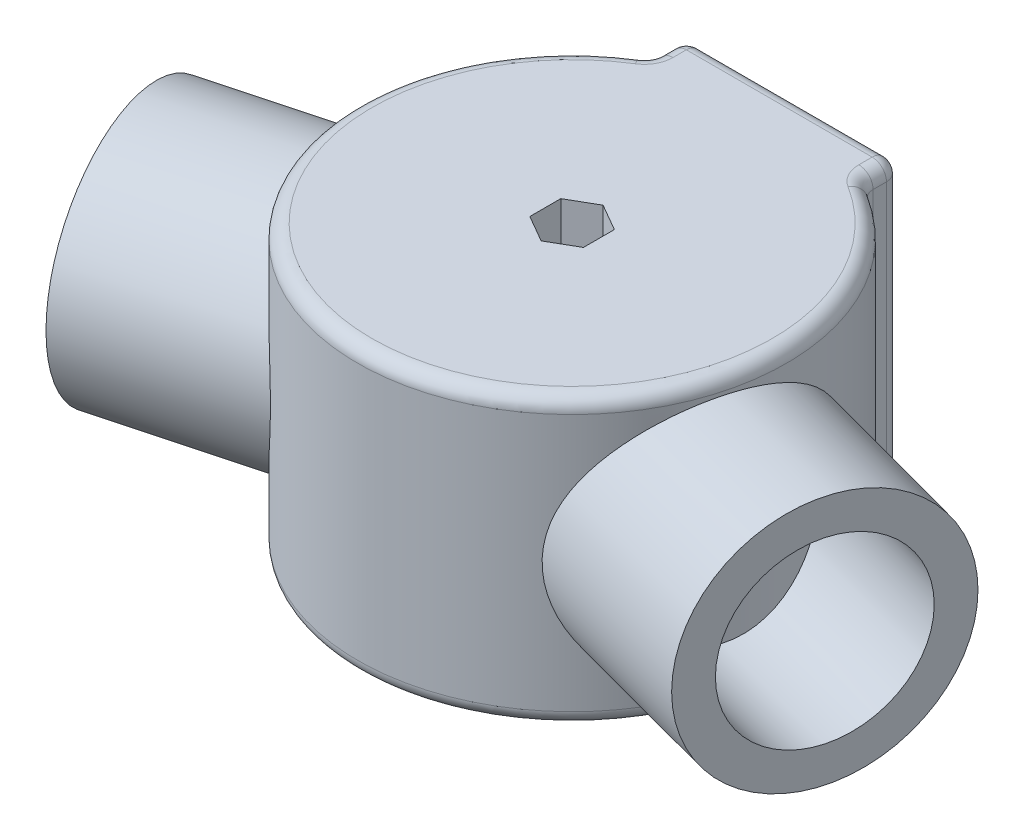
SolidWorks part; units mm, degrees
ref_plane "Front" through (0, 0, 0) normal (0, 0, 1) x (1, 0, 0)
ref_plane "Top" through (0, 0, 0) normal (0, 1, 0) x (1, 0, 0)
ref_plane "Right" through (0, 0, 0) normal (1, 0, 0) x (0, 0, -1)
sketch "Sketch1" plane through (0, 0, 0) normal (0, 1, 0) x (1, 0, 0)
  line L0 (0, 0) -> (0, 39.3456) construction
  line L1 (-19.05, 32.9956) -> (19.05, 32.9956)
  line L2 (-19.05, 32.9956) -> (-19.05, 39.3456)
  line L3 (-19.05, 39.3456) -> (19.05, 39.3456)
  line L4 (19.05, 32.9956) -> (19.05, 39.3456)
  line L6 (0, -5.4993) -> (4.7625, -2.7496)
  line L7 (4.7625, -2.7496) -> (4.7625, 2.7496)
  line L8 (4.7625, 2.7496) -> (0, 5.4993)
  line L9 (0, 5.4993) -> (-4.7625, 2.7496)
  line L10 (-4.7625, 2.7496) -> (-4.7625, -2.7496)
  line L11 (-4.7625, -2.7496) -> (0, -5.4993)
  circle A0 centre (0, 0) radius 38.1
  circle A1 centre (0, 0) radius 4.7625 construction
  dimension "D1" = 76.2
  dimension "D4" = 9.525
  dimension "D2" = 6.35
  dimension "D3" = 38.1
extrude "Boss-Extrude1" add sketch "Sketch1" along normal mid plane 50.8
sketch "Sketch2" plane through (0, 0, 0) normal (0, 1, 0) x (1, 0, 0)
  line L0 (53.9037, -14.4434) -> (0, 0) construction
  line L1 (0, 0) -> (-53.9037, -14.4434) construction
  line L2 (53.9037, -14.4434) -> (-53.9037, -14.4434) construction
  line L6 (-19.05, 39.3456) -> (-19.05, 32.9956)
  line L7 (19.05, 39.3456) -> (-19.05, 39.3456)
  line L8 (19.05, 32.9956) -> (19.05, 39.3456)
  line L9 (-19.05, 39.3456) -> (-19.05, 32.9956)
  line L10 (19.05, 39.3456) -> (-19.05, 39.3456)
  line L11 (19.05, 32.9956) -> (19.05, 39.3456)
  arc A0 (-19.05, 32.9956) -> (19.05, 32.9956) centre (0, 0) ccw construction
  arc A1 (-19.05, 32.9956) -> (19.05, 32.9956) centre (0, 0) ccw
  arc A2 (-19.05, 32.9956) -> (19.05, 32.9956) centre (0, 0) ccw
  point P1 (-36.8018, -9.861)
  point P5 (36.8018, -9.861)
  dimension "D1" = 150
  dimension "D2" = 0
ref_plane "Plane1" through (36.8018, 0, 9.861) normal (-0.9659, 0, -0.2588) x (-0.2588, 0, 0.9659)
sketch "Sketch3" plane through (36.8018, 0, 9.861) normal (-0.9659, 0, -0.2588) x (-0.2588, 0, 0.9659)
  circle A0 centre (0, 0) radius 15.875
  circle A1 centre (0, 0) radius 22.225
  dimension "D1" = 31.75
  dimension "D2" = 6.35
extrude "Boss-Extrude2" add sketch "Sketch3" against normal blind 25.4 and the other way blind 8.255
mirror "Mirror1" about plane through (0, 0, 0) normal (1, 0, 0) of "Boss-Extrude2"
sketch "Sketch5" plane through (0, 0, -39.3456) normal (0, 0, -1) x (-1, 0, 0)
  line L1 (-19.05, 12.7) -> (19.05, 12.7)
  line L2 (-19.05, 12.7) -> (-19.05, -12.7)
  line L3 (-19.05, -12.7) -> (19.05, -12.7)
  line L4 (19.05, 12.7) -> (19.05, -12.7)
  line L5 (-19.05, 12.7) -> (19.05, -12.7) construction
  line L6 (-19.05, -12.7) -> (19.05, 12.7) construction
  point P0 (0, 0)
  dimension "D1" = 38.1
  dimension "D2" = 25.4
ref_plane "Plane2" through (0, 25.4, 0) normal (0, 1, 0) x (1, 0, 0)
fillet "Fillet1" radius 2.54 12 edges at (0, 25.4, 38.1) (0, -25.4, 38.1) (0, 25.4, -39.3456) (0, -25.4, -39.3456) (-19.05, 0, -39.3456) (-19.05, 25.4, -36.1706) (-19.05, 0, -32.9956) (-19.05, -25.4, -36.1706) (19.05, 0, -32.9956) (19.05, 25.4, -36.1706) (19.05, 0, -39.3456) (19.05, -25.4, -36.1706)
